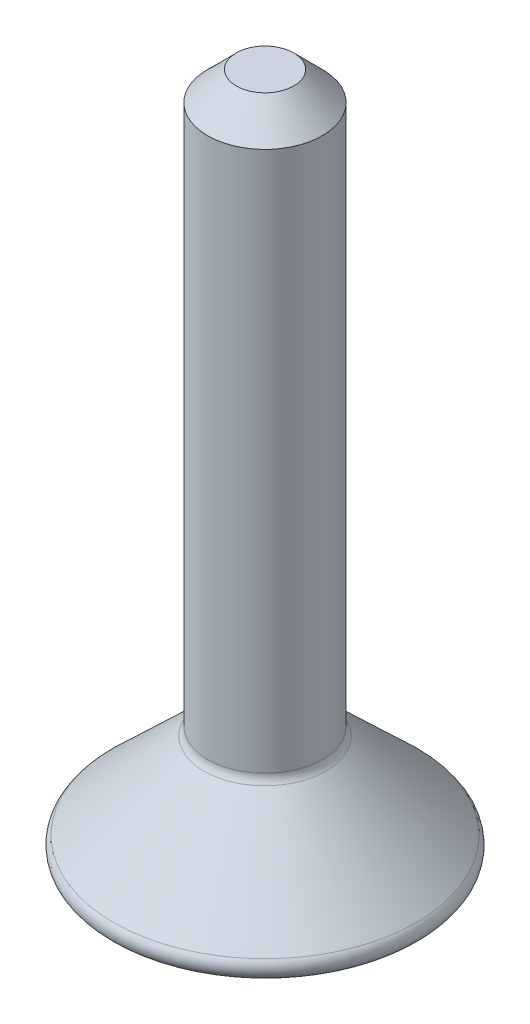
SolidWorks part; units mm, degrees
ref_plane "前视基准面" through (0, 0, 0) normal (0, 0, 1) x (1, 0, 0)
ref_plane "上视基准面" through (0, 0, 0) normal (0, 1, 0) x (1, 0, 0)
ref_plane "右视基准面" through (0, 0, 0) normal (1, 0, 0) x (0, 0, -1)
sketch "草图1" plane through (0, 0, 0) normal (0, 0, 1) x (1, 0, 0)
  line L0 (0, 3.3103) -> (0, -3.8641) construction
  line L1 (0, 1.9) -> (1, 1.9)
  line L2 (1, 1.9) -> (3, 0)
  line L3 (3, 0) -> (0, 0)
  line L4 (0, 1.9) -> (0, 0)
  dimension "D1" = 1
  dimension "D2" = 3
  dimension "D3" = 1.9
revolve "旋转2" add sketch "草图1" angle 360 about L0
sketch "草图2" plane through (0, 1.9, 0) normal (0, 1, 0) x (1, 0, 0)
  circle A0 centre (0, 0) radius 1
  circle A1 centre (0, 0) radius 1 construction
extrude "凸台-拉伸1" add sketch "草图2" along normal blind 10
sketch "草图3" plane through (0, 0, 0) normal (0, -1, 0) x (1, 0, 0)
  line L1 (0, 1.1547) -> (-1, 0.5774)
  line L2 (-1, 0.5774) -> (-1, -0.5774)
  line L3 (-1, -0.5774) -> (0, -1.1547)
  line L4 (0, -1.1547) -> (1, -0.5774)
  line L5 (1, -0.5774) -> (1, 0.5774)
  line L6 (1, 0.5774) -> (0, 1.1547)
  circle A1 centre (0, 0) radius 1 construction
  dimension "D1" = 2
extrude "切除-拉伸1" cut sketch "草图3" against normal blind 1
chamfer "倒角1" distance 0.5 angle 45 1 edges at (0, 11.9, 1)
fillet "圆角1" radius 0.2 2 edges at (0, 1.9, 1) (0, 0, 3)
